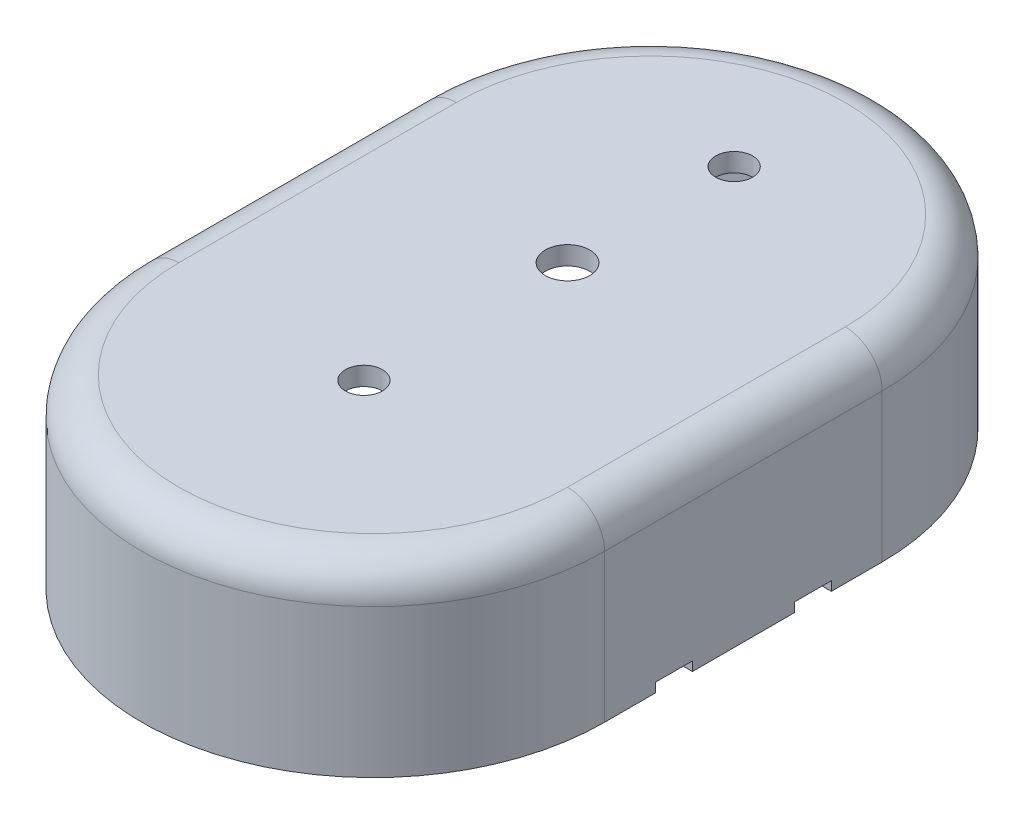
SolidWorks part; units mm, degrees
ref_plane "Front Plane" through (0, 0, 0) normal (0, 0, 1) x (1, 0, 0)
ref_plane "Top Plane" through (0, 0, 0) normal (0, 1, 0) x (1, 0, 0)
ref_plane "Right Plane" through (0, 0, 0) normal (1, 0, 0) x (0, 0, -1)
sketch "Sketch3" plane through (0, 0, 0) normal (0, 1, 0) x (1, 0, 0)
  line L0 (0, 100) -> (0, -100) construction
  line L2 (-62.5, -37.5) -> (-62.5, 37.5)
  line L4 (62.5, -37.5) -> (62.5, 37.5)
  line L8 (0, 0) -> (-62.5, 0) construction
  arc A1 (62.5, 37.5) -> (-62.5, 37.5) centre (0, 37.5) ccw
  arc A2 (62.5, -37.5) -> (-62.5, -37.5) centre (0, -37.5) cw
  point P0 (0, 0)
  dimension "D3" = 62.5
  dimension "D1" = 125
  dimension "D2" = 100
  dimension "D4" = 200
  dimension "D5" = 37.5
  dimension "D6" = 62.5
  dimension "D7" = 100
extrude "Boss-Extrude1" add sketch "Sketch3" along normal blind 50
fillet "Fillet1" radius 10 4 edges at (62.5, 50, 0) (0, 50, 100) (-62.5, 50, 0) (0, 50, -100)
shell "Shell1" thickness 5
sketch "Sketch4" plane through (0, 0, 0) normal (0, -1, 0) x (1, 0, 0)
  line L0 (57.5, 37.5) -> (57.5, -37.5) construction
  line L1 (-57.5, 37.5) -> (-57.5, -37.5) construction
  line L2 (57.5, 37.5) -> (57.5, -37.5) construction
  line L3 (-57.5, 37.5) -> (-57.5, -37.5) construction
  line L4 (-60, 37.5) -> (-60, -37.5)
  line L5 (60, 37.5) -> (60, -37.5)
  arc A0 (-57.5, -37.5) -> (57.5, -37.5) centre (0, -37.5) ccw construction
  arc A1 (57.5, 37.5) -> (-57.5, 37.5) centre (0, 37.5) ccw construction
  arc A2 (-57.5, -37.5) -> (57.5, -37.5) centre (0, -37.5) ccw construction
  arc A3 (57.5, 37.5) -> (-57.5, 37.5) centre (0, 37.5) ccw construction
  arc A4 (60, 37.5) -> (-60, 37.5) centre (0, 37.5) ccw
  arc A5 (-60, -37.5) -> (60, -37.5) centre (0, -37.5) ccw
  dimension "D1" = 2.5
extrude "Cut-Extrude2" cut sketch "Sketch4" against normal blind 2.5
sketch "Sketch5" plane through (-62.5, 0, 0) normal (-1, 0, 0) x (0, 0, 1)
  line L0 (0, 2.5) -> (-37.5, 2.5) construction
  line L2 (0, 0) -> (0, 2.5) construction
  line L3 (-37.5, 40) -> (-37.5, 0) construction
  line L4 (0, 2.5) -> (37.5, 2.5) construction
  line L5 (37.5, 40) -> (37.5, 0) construction
  line L6 (-18.75, 2.5) -> (-18.75, 0) construction
  line L7 (-37.5, 0) -> (37.5, 0) construction
  line L8 (-23.75, 0) -> (-23.75, 2.5)
  line L9 (-23.75, 0) -> (-13.75, 0)
  line L11 (-23.75, 2.5) -> (-13.75, 2.5)
  line L12 (-13.75, 0) -> (-13.75, 2.5)
  line L13 (23.75, 0) -> (23.75, 2.5)
  line L14 (23.75, 0) -> (13.75, 0)
  line L15 (13.75, 0) -> (13.75, 2.5)
  line L16 (23.75, 2.5) -> (13.75, 2.5)
  dimension "D1" = 2.5
  dimension "D2" = 37.5
  dimension "D3" = 10
extrude "Cut-Extrude3" cut sketch "Sketch5" against normal through all
sketch "Sketch6" plane through (0, 50, 0) normal (0, 1, 0) x (1, 0, 0)
  line L0 (0, 90) -> (0, -90) construction
  arc A0 (52.5, 37.5) -> (-52.5, 37.5) centre (0, 37.5) ccw construction
  arc A1 (-52.5, -37.5) -> (52.5, -37.5) centre (0, -37.5) ccw construction
  circle A2 centre (0, 60) radius 5
  circle A3 centre (0, 15) radius 6
  circle A4 centre (0, -40) radius 5
  dimension "D1" = 10
  dimension "D3" = 12
  dimension "D6" = 10
  dimension "D2" = 30
  dimension "D4" = 75
  dimension "D5" = 50
extrude "Cut-Extrude4" cut sketch "Sketch6" against normal up to next
